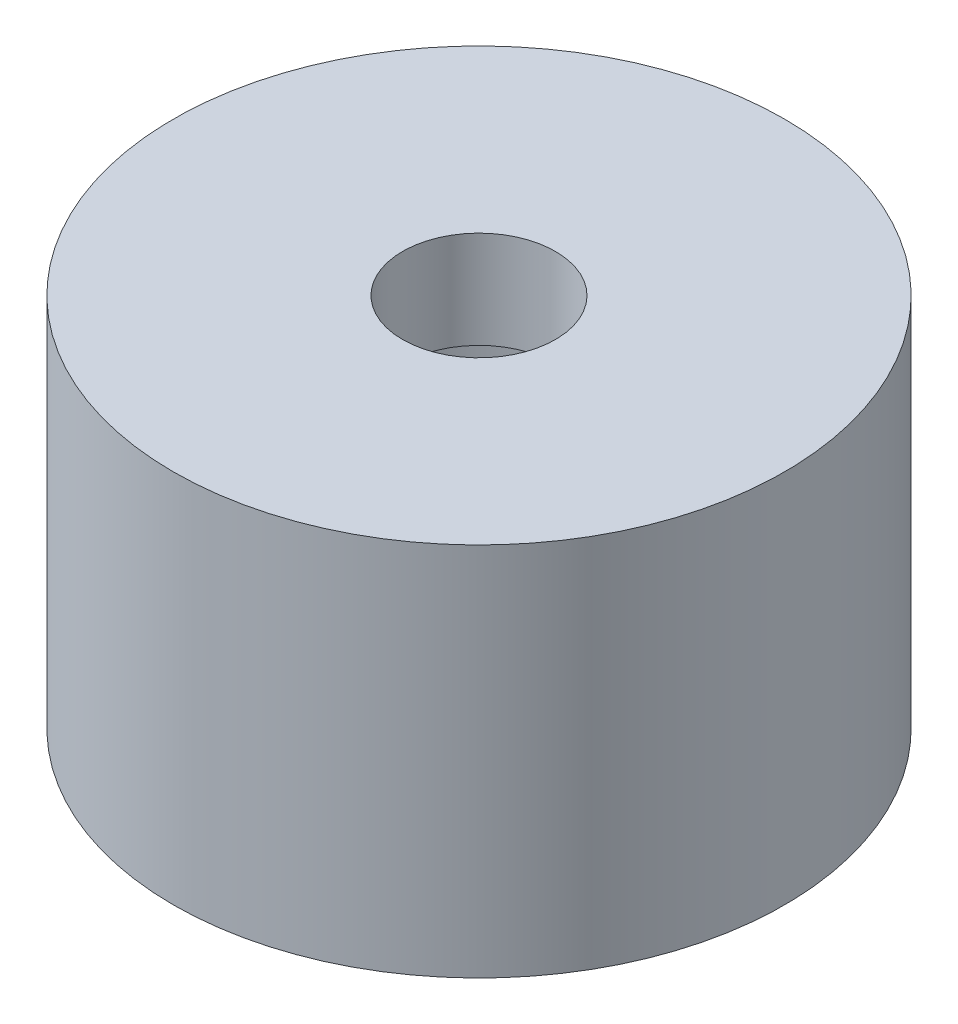
SolidWorks part; units mm, degrees
ref_plane "Front Plane" through (0, 0, 0) normal (0, 0, 1) x (1, 0, 0)
ref_plane "Top Plane" through (0, 0, 0) normal (0, 1, 0) x (1, 0, 0)
ref_plane "Right Plane" through (0, 0, 0) normal (1, 0, 0) x (0, 0, -1)
sketch "Sketch1" plane through (0, 0, 0) normal (0, 1, 0) x (1, 0, 0)
  circle A0 centre (0, 0) radius 7
  circle A1 centre (0, 0) radius 11
  dimension "D1" = 22
  dimension "D2" = 14
extrude "Boss-Extrude1" add sketch "Sketch1" along normal blind 10 contours A1
sketch "Sketch2" plane through (0, 10, 0) normal (0, 1, 0) x (1, 0, 0)
  circle A0 centre (0, 0) radius 2.75
  circle A1 centre (0, 0) radius 11
  circle A2 centre (0, 0) radius 11
  dimension "D2" = 5.5
  dimension "D1" = 0
extrude "Boss-Extrude2" add sketch "Sketch2" along normal blind 3.5
